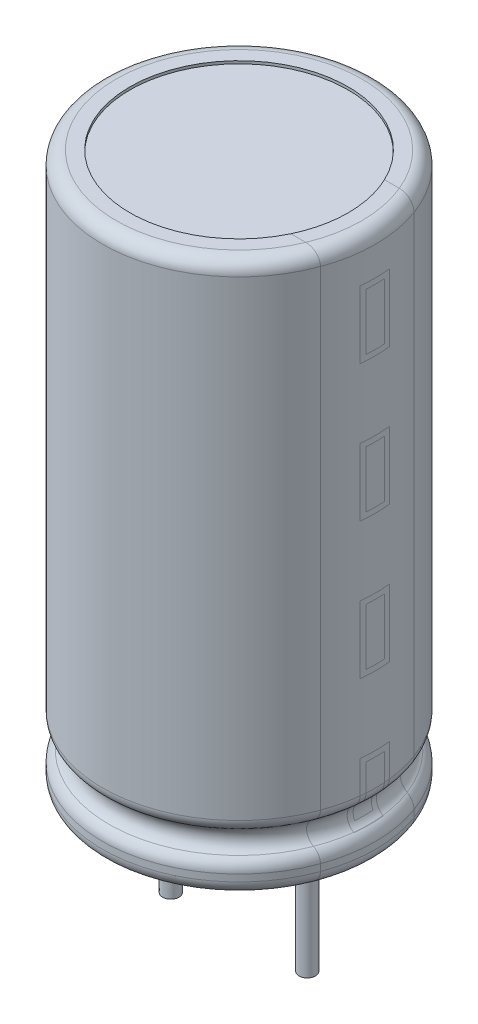
SolidWorks part; units mm, degrees
ref_plane "Front Plane" through (0, 0, 0) normal (0, 0, 1) x (1, 0, 0)
ref_plane "Top Plane" through (0, 0, 0) normal (0, 1, 0) x (1, 0, 0)
ref_plane "Right Plane" through (0, 0, 0) normal (1, 0, 0) x (0, 0, -1)
sketch "Sketch1" plane through (0, 0, 0) normal (0, 1, 0) x (1, 0, 0)
  line L0 (0, 0) -> (0, 44.7542) construction
  line L1 (0, 0) -> (-44.7542, 0) construction
  circle A0 centre (-2.5, 0) radius 0.3
  circle A1 centre (2.5, 0) radius 0.3
  dimension "D3" = 0.6
  dimension "D1" = 2.5
extrude "Boss-Extrude1" add sketch "Sketch1" against normal blind 4.72
sketch "Sketch3" plane through (0, 0, 0) normal (0, 0, 1) x (1, 0, 0)
  line L0 (0, 0) -> (-4.6285, 0) construction
  line L1 (0, 0) -> (0, 20.1) construction
  line L2 (5, 0.4) -> (5, 0.6505)
  line L3 (0, 0) -> (4, 0)
  line L4 (4, 20.1) -> (4.5, 20.1)
  line L5 (4, -0.1) -> (4.5, -0.1)
  line L6 (0, 20) -> (4, 20)
  line L7 (5, 2.3495) -> (5, 19.6)
  line L8 (4, 20) -> (4, 20.1)
  line L9 (5, 2.3495) -> (5, 20.1) construction
  line L10 (4, -0.1) -> (4, 0)
  line L11 (0, 20) -> (5, 20) construction
  line L12 (0, 20.1) -> (5, 20.1) construction
  line L13 (4, 2.3495) -> (4, 20.1) construction
  line L14 (0, 0) -> (0, 20)
  line L17 (0, 0) -> (5, 0) construction
  line L18 (0, -0.1) -> (5, -0.1) construction
  arc A0 (4.7644, 1.9251) -> (4.7644, 1.0749) centre (5.0292, 1.5) ccw
  arc A1 (5, 0.6505) -> (4.7644, 1.0749) centre (4.5, 0.6505) ccw
  arc A2 (5, 2.3495) -> (4.7644, 1.9251) centre (4.5, 2.3495) cw
  arc A3 (5, 19.6) -> (4.5, 20.1) centre (4.5, 19.6) ccw
  arc A4 (4.5, -0.1) -> (5, 0.4) centre (4.5, 0.4) ccw
  point P13 (5, 2)
  dimension "D2" = 0.5
  dimension "D1" = 0.5
  dimension "D3" = 20
  dimension "D6" = 5
  dimension "D4" = 0.1
  dimension "D5" = 1
revolve "Revolve1" add sketch "Sketch3" angle 360 about L14
sketch "Sketch4" plane through (0, 0, 0) normal (1, 0, 0) x (0, 0, -1)
  line L0 (-4.5, -0.1) -> (4.5, -0.1) construction
  line L1 (-1.7148, -0.1) -> (1.7148, -0.1)
  line L2 (0, -0.1) -> (0, 20.1) construction
  line L3 (-1.7148, 20.1) -> (1.7148, 20.1)
  line L4 (1.7148, -0.1) -> (1.7148, 20.1)
  line L5 (4, 20.1) -> (-4, 20.1) construction
  line L6 (-1.7148, -0.1) -> (-1.7148, 20.1)
  line L7 (-0.3349, 13.3362) -> (-0.3349, 11.2664)
  line L8 (-0.3349, 13.3362) -> (0.3349, 13.3362)
  line L9 (0, 13.3362) -> (0, 11.2664) construction
  line L10 (-0.3349, 11.2664) -> (0.3349, 11.2664)
  line L11 (0.3349, 13.3362) -> (0.3349, 11.2664)
  line L12 (0.5349, 13.5362) -> (0.5349, 11.0664)
  line L13 (-0.5349, 11.0664) -> (0.5349, 11.0664)
  line L14 (-0.5349, 13.5362) -> (-0.5349, 11.0664)
  line L15 (-0.5349, 13.5362) -> (0.5349, 13.5362)
  line L16 (0, -0.1) -> (0, -3.7489) construction
  line L17 (-0.3349, 8.3362) -> (-0.3349, 6.2664)
  line L18 (-0.3349, 8.3362) -> (0.3349, 8.3362)
  line L19 (-0.3349, 6.2664) -> (0.3349, 6.2664)
  line L20 (0.3349, 8.3362) -> (0.3349, 6.2664)
  line L21 (0.5349, 8.5362) -> (0.5349, 6.0664)
  line L22 (-0.5349, 6.0664) -> (0.5349, 6.0664)
  line L23 (-0.5349, 8.5362) -> (-0.5349, 6.0664)
  line L24 (-0.5349, 8.5362) -> (0.5349, 8.5362)
  line L25 (0, 8.3362) -> (0, 6.2664) construction
  line L26 (-0.3349, 3.3362) -> (-0.3349, 1.2664)
  line L27 (-0.3349, 3.3362) -> (0.3349, 3.3362)
  line L28 (-0.3349, 1.2664) -> (0.3349, 1.2664)
  line L29 (0.3349, 3.3362) -> (0.3349, 1.2664)
  line L30 (0.5349, 3.5362) -> (0.5349, 1.0664)
  line L31 (-0.5349, 1.0664) -> (0.5349, 1.0664)
  line L32 (-0.5349, 3.5362) -> (-0.5349, 1.0664)
  line L33 (-0.5349, 3.5362) -> (0.5349, 3.5362)
  line L34 (0, 3.3362) -> (0, 1.2664) construction
  line L35 (-0.5349, 18.5362) -> (0.5349, 18.5362)
  line L36 (-0.5349, 18.5362) -> (-0.5349, 16.0664)
  line L37 (-0.3349, 18.3362) -> (0.3349, 18.3362)
  line L38 (0.3349, 18.3362) -> (0.3349, 16.2664)
  line L39 (0.5349, 18.5362) -> (0.5349, 16.0664)
  line L40 (-0.3349, 18.3362) -> (-0.3349, 16.2664)
  line L41 (-0.3349, 16.2664) -> (0.3349, 16.2664)
  line L42 (-0.5349, 16.0664) -> (0.5349, 16.0664)
  line L43 (-0.5349, 23.5362) -> (0.5349, 23.5362)
  line L44 (-0.5349, 23.5362) -> (-0.5349, 21.0664)
  line L45 (-0.3349, 23.3362) -> (-0.3349, 21.2664)
  line L46 (-0.3349, 23.3362) -> (0.3349, 23.3362)
  line L47 (0.3349, 23.3362) -> (0.3349, 21.2664)
  line L48 (0.5349, 23.5362) -> (0.5349, 21.0664)
  line L49 (-0.3349, 21.2664) -> (0.3349, 21.2664)
  line L50 (-0.5349, 21.0664) -> (0.5349, 21.0664)
  dimension "D1" = 0.2
  dimension "D2" = 3
  dimension "D3" = 2
  dimension "D4" = 2
split line "Split Line1"
